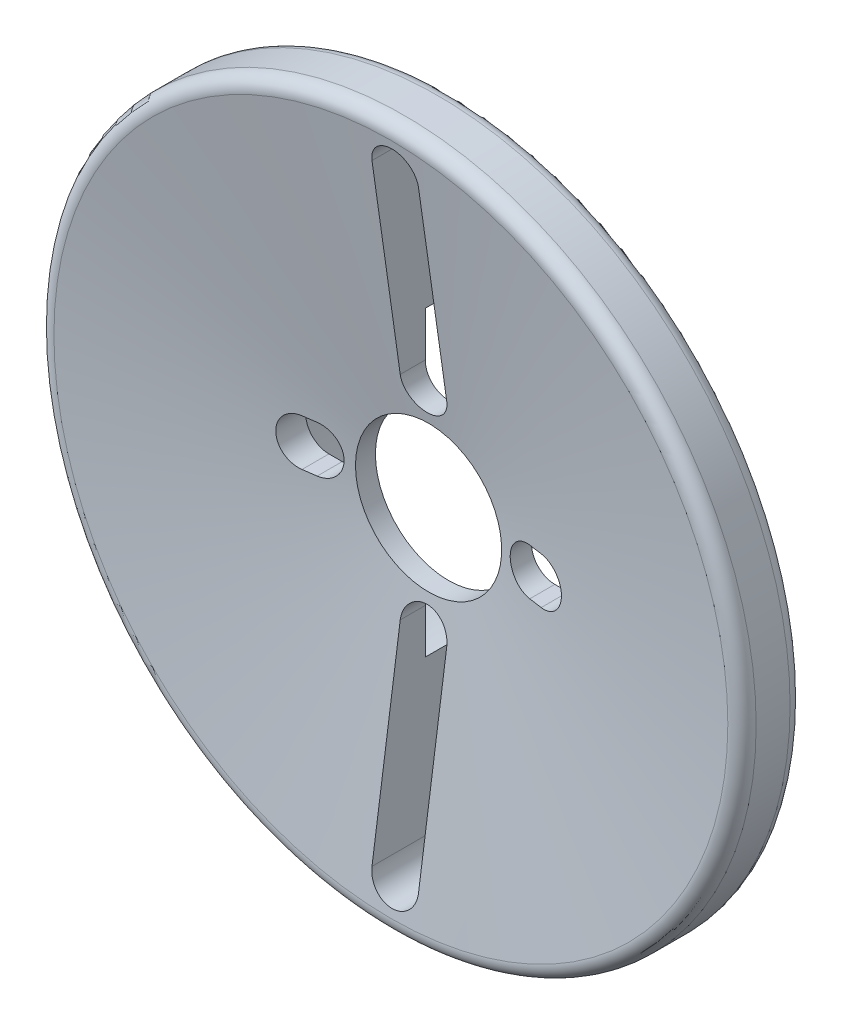
SolidWorks part; units mm, degrees
material "ABS"
ref_plane "Front Plane" through (0, 0, 0) normal (0, 0, 1) x (1, 0, 0)
ref_plane "Top Plane" through (0, 0, 0) normal (0, 1, 0) x (1, 0, 0)
ref_plane "Right Plane" through (0, 0, 0) normal (1, 0, 0) x (0, 0, -1)
sketch "Sketch1" plane through (0, 0, 0) normal (0, 0, 1) x (1, 0, 0)
  circle A0 centre (0, 0) radius 5.5
  circle A2 centre (0, 0) radius 26.5
  dimension "D1" = 11
  dimension "D2" = 21
extrude "Boss-Extrude1" add sketch "Sketch1" along normal blind 1.5
sketch "Sketch8" plane through (0, 0, 0) normal (0, 1, 0) x (1, 0, 0)
  line L0 (26.5, 0) -> (-26.5, 0) construction
  line L1 (26.5, 0) -> (-11.5, 0) construction
  line L2 (0, 0) -> (0, -17.1822) construction
  line L3 (-11.5, 0) -> (-11.5, 3.5)
  line L4 (-11.5, 3.5) -> (26.5, 0) construction
  line L5 (11.5, 3.5) -> (-26.5, 0) construction
  line L6 (11.5, 0) -> (11.5, 3.5) construction
  line L7 (11.5, 0) -> (-26.5, 0) construction
  line L8 (-11.5, 3.5) -> (-26.5, 0)
  line L9 (-26.5, 0) -> (-11.5, 0)
  line L10 (-26.5, -1.5) -> (26.5, -1.5) construction
  line L11 (5.5, -1.5) -> (26.5, -1.5)
  line L13 (26.5, -1.5) -> (26.5, -4.5)
  line L14 (26.5, -4.5) -> (5.5, -1.5)
  point P10 (11.5, 1.75)
  dimension "D1" = 23
  dimension "D2" = 3.5
  dimension "D3" = 3
revolve "Revolve2" add sketch "Sketch8" angle 360 about L2
sketch "Sketch7" plane through (0, 0, 0) normal (0, 0, 1) x (1, 0, 0)
  line L0 (1.75, -8) -> (1.75, -23)
  line L1 (-1.75, -8) -> (-1.75, -23)
  line L6 (8, 1.75) -> (9, 1.75)
  line L7 (8, -1.75) -> (9, -1.75)
  circle A0 centre (0, 0) radius 8 construction
  arc A1 (1.75, -8) -> (-1.75, -8) centre (0, -8) ccw
  arc A7 (8, 1.75) -> (8, -1.75) centre (8, 0) ccw
  arc A8 (-1.75, -23) -> (1.75, -23) centre (0, -23) ccw
  arc A11 (9, -1.75) -> (9, 1.75) centre (9, 0) ccw
  arc A12 (-8, -1.75) -> (-8, 1.75) centre (-8, 0) ccw [skipped]
  arc A13 (-1.75, 8) -> (1.75, 8) centre (0, 8) ccw [skipped]
  point P14 (0, 0)
  point P15 (0, 0)
  point P35 (0, 0)
  dimension "D1" = 16
  dimension "D2" = 3.5
  dimension "D4" = 15
  dimension "D5" = 1
  dimension "D6" = 90
  dimension "D3" = 4
extrude "holes" cut sketch "Sketch7" along normal through all both and the other way through all contours A7
fillet "Fillet2" radius 1 2 edges at (-26.5, 0, 0) (-26.5, 0, 4.5)
pattern_circular "holes-ptr" count 2 over 360 about axis through (0, 0, 0) along (0, 0, 1) of "holes"
